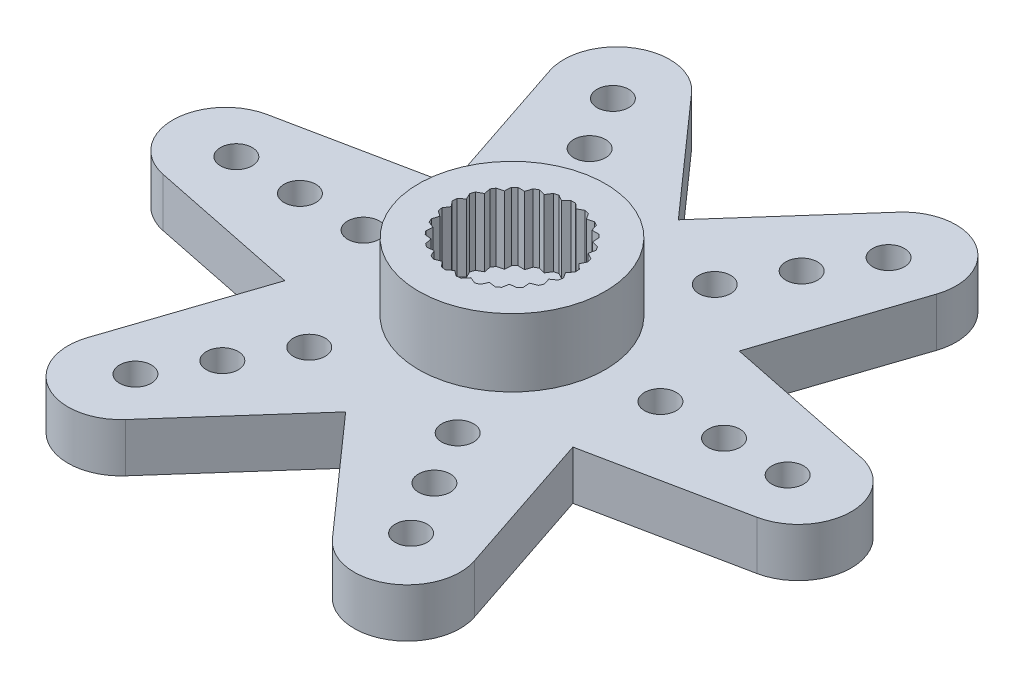
SolidWorks part; units mm, degrees
material "ABS"
ref_plane "Front Plane" through (0, 0, 0) normal (0, 0, 1) x (1, 0, 0)
ref_plane "Top Plane" through (0, 0, 0) normal (0, 1, 0) x (1, 0, 0)
ref_plane "Right Plane" through (0, 0, 0) normal (1, 0, 0) x (0, 0, -1)
sketch "Sketch2" plane through (0, 0, 0) normal (0, 1, 0) x (1, 0, 0)
  circle A0 centre (0, 0) radius 6
  circle A1 centre (0, 0) radius 1.5
  dimension "D1" = 12
  dimension "D2" = 3
extrude "Boss-Extrude1" add sketch "Sketch2" along normal mid plane 2.3
sketch "Sketch3" plane through (0, 1.15, 0) normal (0, 1, 0) x (1, 0, 0)
  line L0 (0, 0) -> (0, 2.9) construction
  line L3 (0, 0) -> (0.376, 2.9763) construction
  line L52 (0.1074, 2.898) -> (0.3384, 2.6787)
  line L53 (-0.1074, 2.898) -> (-0.3384, 2.6787)
  line L54 (0.8248, 2.7802) -> (0.9939, 2.5104)
  line L55 (0.6167, 2.8337) -> (0.3384, 2.6787)
  line L56 (1.4903, 2.4878) -> (1.587, 2.1843)
  line L57 (1.302, 2.5913) -> (0.9939, 2.5104)
  line L58 (2.0621, 2.039) -> (2.0804, 1.721)
  line L59 (1.9055, 2.1861) -> (1.587, 2.1843)
  line L60 (2.5044, 1.4621) -> (2.443, 1.1496)
  line L61 (2.3893, 1.6435) -> (2.0804, 1.721)
  line L62 (2.7894, 0.7934) -> (2.6522, 0.5059)
  line L63 (2.723, 0.9977) -> (2.443, 1.1496)
  line L64 (2.899, 0.0748) -> (2.6947, -0.1695)
  line L65 (2.8855, 0.2892) -> (2.6522, 0.5059)
  line L66 (2.8265, -0.6486) -> (2.5679, -0.8343)
  line L67 (2.8668, -0.4375) -> (2.6947, -0.1695)
  line L68 (2.5765, -1.3311) -> (2.2797, -1.4467)
  line L69 (2.6679, -1.1367) -> (2.5679, -0.8343)
  line L70 (2.1645, -1.93) -> (1.8483, -1.9682)
  line L71 (2.3014, -1.7645) -> (2.2797, -1.4467)
  line L72 (1.6165, -2.4077) -> (1.3007, -2.366)
  line L73 (1.7903, -2.2814) -> (1.8483, -1.9682)
  line L74 (0.967, -2.734) -> (0.6715, -2.6152)
  line L75 (1.1667, -2.655) -> (1.3007, -2.366)
  line L76 (0.2566, -2.8886) -> (0, -2.7)
  line L77 (0.4698, -2.8617) -> (0.6715, -2.6152)
  line L78 (-0.4698, -2.8617) -> (-0.6715, -2.6152)
  line L79 (-0.2566, -2.8886) -> (0, -2.7)
  line L80 (-1.1667, -2.655) -> (-1.3007, -2.366)
  line L81 (-0.967, -2.734) -> (-0.6715, -2.6152)
  line L82 (-1.7903, -2.2814) -> (-1.8483, -1.9682)
  line L83 (-1.6165, -2.4077) -> (-1.3007, -2.366)
  line L84 (-2.3014, -1.7645) -> (-2.2797, -1.4467)
  line L85 (-2.1645, -1.93) -> (-1.8483, -1.9682)
  line L86 (-2.6679, -1.1367) -> (-2.5679, -0.8343)
  line L87 (-2.5765, -1.3311) -> (-2.2797, -1.4467)
  line L88 (-2.8668, -0.4375) -> (-2.6947, -0.1695)
  line L89 (-2.8265, -0.6486) -> (-2.5679, -0.8343)
  line L90 (-2.8855, 0.2892) -> (-2.6522, 0.5059)
  line L91 (-2.899, 0.0748) -> (-2.6947, -0.1695)
  line L92 (-2.723, 0.9977) -> (-2.443, 1.1496)
  line L93 (-2.7894, 0.7934) -> (-2.6522, 0.5059)
  line L94 (-2.3893, 1.6435) -> (-2.0804, 1.721)
  line L95 (-2.5044, 1.4621) -> (-2.443, 1.1496)
  line L96 (-1.9055, 2.1861) -> (-1.587, 2.1843)
  line L97 (-2.0621, 2.039) -> (-2.0804, 1.721)
  line L98 (-1.302, 2.5913) -> (-0.9939, 2.5104)
  line L99 (-1.4903, 2.4878) -> (-1.587, 2.1843)
  line L100 (-0.6167, 2.8337) -> (-0.3384, 2.6787)
  line L101 (-0.8248, 2.7802) -> (-0.9939, 2.5104)
  line L102 (-2.533, 1.6075) -> (-2.3893, 1.6435) construction
  line L103 (-2.533, 1.6075) -> (-2.5044, 1.4621) construction
  line L104 (-2.8532, 0.9271) -> (-2.723, 0.9977) construction
  line L105 (-2.8532, 0.9271) -> (-2.7894, 0.7934) construction
  line L106 (-2.9941, 0.1884) -> (-2.8855, 0.2892) construction
  line L107 (-2.9941, 0.1884) -> (-2.899, 0.0748) construction
  line L108 (-2.9469, -0.5621) -> (-2.8668, -0.4375) construction
  line L109 (-2.9469, -0.5621) -> (-2.8265, -0.6486) construction
  line L110 (0, 3) -> (0.1074, 2.898) construction
  line L111 (0, 2.9) -> (0, 3) construction
  line L112 (0, 3) -> (-0.1074, 2.898) construction
  line L113 (-0.7461, 2.9057) -> (-0.6167, 2.8337) construction
  line L114 (-0.7461, 2.9057) -> (-0.8248, 2.7802) construction
  line L115 (-1.4453, 2.6289) -> (-1.302, 2.5913) construction
  line L116 (-1.4453, 2.6289) -> (-1.4903, 2.4878) construction
  line L117 (-2.0536, 2.1869) -> (-1.9055, 2.1861) construction
  line L118 (-2.0536, 2.1869) -> (-2.0621, 2.039) construction
  line L119 (-2.7145, -1.2773) -> (-2.6679, -1.1367) construction
  line L120 (-2.7145, -1.2773) -> (-2.5765, -1.3311) construction
  line L121 (-2.3115, -1.9123) -> (-2.3014, -1.7645) construction
  line L122 (-2.3115, -1.9123) -> (-2.1645, -1.93) construction
  line L123 (-1.7634, -2.4271) -> (-1.7903, -2.2814) construction
  line L124 (-1.7634, -2.4271) -> (-1.6165, -2.4077) construction
  line L125 (-1.1044, -2.7893) -> (-1.1667, -2.655) construction
  line L126 (-1.1044, -2.7893) -> (-0.967, -2.734) construction
  line L127 (-0.376, -2.9763) -> (-0.4698, -2.8617) construction
  line L128 (-0.376, -2.9763) -> (-0.2566, -2.8886) construction
  line L129 (0.376, -2.9763) -> (0.2566, -2.8886) construction
  line L130 (0.376, -2.9763) -> (0.4698, -2.8617) construction
  line L131 (1.1044, -2.7893) -> (0.967, -2.734) construction
  line L132 (1.1044, -2.7893) -> (1.1667, -2.655) construction
  line L133 (1.7634, -2.4271) -> (1.6165, -2.4077) construction
  line L134 (1.7634, -2.4271) -> (1.7903, -2.2814) construction
  line L135 (2.3115, -1.9123) -> (2.3014, -1.7645) construction
  line L136 (2.3115, -1.9123) -> (2.1645, -1.93) construction
  line L137 (2.7145, -1.2773) -> (2.6679, -1.1367) construction
  line L138 (2.7145, -1.2773) -> (2.5765, -1.3311) construction
  line L139 (2.9469, -0.5621) -> (2.8668, -0.4375) construction
  line L140 (2.9469, -0.5621) -> (2.8265, -0.6486) construction
  line L141 (2.9941, 0.1884) -> (2.8855, 0.2892) construction
  line L142 (2.9941, 0.1884) -> (2.899, 0.0748) construction
  line L143 (2.8532, 0.9271) -> (2.723, 0.9977) construction
  line L144 (2.8532, 0.9271) -> (2.7894, 0.7934) construction
  line L145 (2.533, 1.6075) -> (2.3893, 1.6435) construction
  line L146 (2.533, 1.6075) -> (2.5044, 1.4621) construction
  line L147 (2.0536, 2.1869) -> (1.9055, 2.1861) construction
  line L148 (2.0536, 2.1869) -> (2.0621, 2.039) construction
  line L149 (1.4453, 2.6289) -> (1.302, 2.5913) construction
  line L150 (1.4453, 2.6289) -> (1.4903, 2.4878) construction
  line L151 (0.7461, 2.9057) -> (0.6167, 2.8337) construction
  line L152 (0.7461, 2.9057) -> (0.8248, 2.7802) construction
  circle A0 centre (0, 0) radius 4.4
  circle A1 centre (0, 0) radius 3 construction
  circle A2 centre (0, 0) radius 2.7 construction
  arc A3 (-0.6167, 2.8337) -> (-0.8248, 2.7802) centre (0, 0) ccw
  arc A4 (-0.1074, 2.898) -> (-0.6167, 2.8337) centre (0, 0) ccw construction
  arc A5 (-0.8248, 2.7802) -> (-1.302, 2.5913) centre (0, 0) ccw construction
  arc A6 (-1.302, 2.5913) -> (-1.4903, 2.4878) centre (0, 0) ccw
  arc A7 (-1.4903, 2.4878) -> (-1.9055, 2.1861) centre (0, 0) ccw construction
  arc A8 (-1.9055, 2.1861) -> (-2.0621, 2.039) centre (0, 0) ccw
  arc A9 (-2.0621, 2.039) -> (-2.3893, 1.6435) centre (0, 0) ccw construction
  arc A10 (-2.3893, 1.6435) -> (-2.5044, 1.4621) centre (0, 0) ccw
  arc A11 (-2.5044, 1.4621) -> (-2.723, 0.9977) centre (0, 0) ccw construction
  arc A12 (-2.723, 0.9977) -> (-2.7894, 0.7934) centre (0, 0) ccw
  arc A13 (-2.7894, 0.7934) -> (-2.8855, 0.2892) centre (0, 0) ccw construction
  arc A14 (-2.8855, 0.2892) -> (-2.899, 0.0748) centre (0, 0) ccw
  arc A15 (-2.899, 0.0748) -> (-2.8668, -0.4375) centre (0, 0) ccw construction
  arc A16 (-2.8668, -0.4375) -> (-2.8265, -0.6486) centre (0, 0) ccw
  arc A17 (-2.8265, -0.6486) -> (-2.6679, -1.1367) centre (0, 0) ccw construction
  arc A18 (-2.6679, -1.1367) -> (-2.5765, -1.3311) centre (0, 0) ccw
  arc A19 (-2.5765, -1.3311) -> (-2.3014, -1.7645) centre (0, 0) ccw construction
  arc A20 (-2.3014, -1.7645) -> (-2.1645, -1.93) centre (0, 0) ccw
  arc A21 (-2.1645, -1.93) -> (-1.7903, -2.2814) centre (0, 0) ccw construction
  arc A22 (-1.7903, -2.2814) -> (-1.6165, -2.4077) centre (0, 0) ccw
  arc A23 (-1.6165, -2.4077) -> (-1.1667, -2.655) centre (0, 0) ccw construction
  arc A24 (-1.1667, -2.655) -> (-0.967, -2.734) centre (0, 0) ccw
  arc A25 (-0.967, -2.734) -> (-0.4698, -2.8617) centre (0, 0) ccw construction
  arc A26 (-0.4698, -2.8617) -> (-0.2566, -2.8886) centre (0, 0) ccw
  arc A27 (-0.2566, -2.8886) -> (0.2566, -2.8886) centre (0, 0) ccw construction
  arc A28 (0.2566, -2.8886) -> (0.4698, -2.8617) centre (0, 0) ccw
  arc A29 (0.4698, -2.8617) -> (0.967, -2.734) centre (0, 0) ccw construction
  arc A30 (0.967, -2.734) -> (1.1667, -2.655) centre (0, 0) ccw
  arc A31 (1.1667, -2.655) -> (1.6165, -2.4077) centre (0, 0) ccw construction
  arc A32 (1.6165, -2.4077) -> (1.7903, -2.2814) centre (0, 0) ccw
  arc A33 (1.7903, -2.2814) -> (2.1645, -1.93) centre (0, 0) ccw construction
  arc A34 (2.1645, -1.93) -> (2.3014, -1.7645) centre (0, 0) ccw
  arc A35 (2.3014, -1.7645) -> (2.5765, -1.3311) centre (0, 0) ccw construction
  arc A36 (2.5765, -1.3311) -> (2.6679, -1.1367) centre (0, 0) ccw
  arc A37 (2.6679, -1.1367) -> (2.8265, -0.6486) centre (0, 0) ccw construction
  arc A38 (2.8265, -0.6486) -> (2.8668, -0.4375) centre (0, 0) ccw
  arc A39 (2.8668, -0.4375) -> (2.899, 0.0748) centre (0, 0) ccw construction
  arc A40 (2.899, 0.0748) -> (2.8855, 0.2892) centre (0, 0) ccw
  arc A41 (2.8855, 0.2892) -> (2.7894, 0.7934) centre (0, 0) ccw construction
  arc A42 (2.7894, 0.7934) -> (2.723, 0.9977) centre (0, 0) ccw
  arc A43 (2.723, 0.9977) -> (2.5044, 1.4621) centre (0, 0) ccw construction
  arc A44 (2.5044, 1.4621) -> (2.3893, 1.6435) centre (0, 0) ccw
  arc A45 (2.3893, 1.6435) -> (2.0621, 2.039) centre (0, 0) ccw construction
  arc A46 (2.0621, 2.039) -> (1.9055, 2.1861) centre (0, 0) ccw
  arc A47 (1.9055, 2.1861) -> (1.4903, 2.4878) centre (0, 0) ccw construction
  arc A48 (1.4903, 2.4878) -> (1.302, 2.5913) centre (0, 0) ccw
  arc A49 (1.302, 2.5913) -> (0.8248, 2.7802) centre (0, 0) ccw construction
  arc A50 (0.8248, 2.7802) -> (0.6167, 2.8337) centre (0, 0) ccw
  arc A51 (0.3635, 2.8771) -> (0.1074, 2.898) centre (0, 0) ccw construction
  arc A52 (0.1074, 2.898) -> (-0.1074, 2.898) centre (0, 0) ccw
  arc A53 (0.6167, 2.8337) -> (0.3635, 2.8771) centre (0, 0) ccw construction
  point P84 (0, 0)
  dimension "D1" = 8.8
  dimension "D2" = 5.4
  dimension "D3" = 6
  dimension "D6" = 5.8
  dimension "D4" = 7.2
  dimension "D5" = 25
extrude "Boss-Extrude2" add sketch "Sketch3" along normal blind 3.2
sketch "Sketch4" plane through (0, 0, 0) normal (0, 1, 0) x (1, 0, 0)
  line L0 (0, 0) -> (13, 0) construction
  line L1 (3.9686, 4.5) -> (14.0007, 2.4494)
  line L2 (3.9686, -4.5) -> (14.0007, -2.4494)
  line L3 (13, 0) -> (10, 0) construction
  circle A0 centre (0, 0) radius 6 construction
  arc A1 (3.9686, -4.5) -> (3.9686, 4.5) centre (0, 0) ccw
  arc A2 (14.0007, 2.4494) -> (14.0007, -2.4494) centre (13.5, 0) cw
  circle A3 centre (13, 0) radius 0.75
  circle A4 centre (10, 0) radius 0.75
  circle A5 centre (7, 0) radius 0.75
  dimension "D3" = 2.5
  dimension "D5" = 1.5
  dimension "D2" = 9
  dimension "D7" = 3
  dimension "D4" = 0.5
  dimension "D1" = 13
  dimension "D6" = 3
extrude "Boss-Extrude3" add sketch "Sketch4" along normal mid plane 2.3
pattern_circular "CirPattern1" count 6 over 360 about axis through (0, 0, 0) along (0, 1, 0) of "Boss-Extrude3"
sketch "Sketch5" [suppressed] plane through (0, 0, 0) normal (0, 1, 0) x (1, 0, 0)
  line L0 (3, 7) -> (-3, 7) construction
  circle A0 centre (0, 0) radius 10
  circle A1 centre (0, 7) radius 0.75
  circle A2 centre (-3, 7) radius 0.75
  circle A3 centre (3, 7) radius 0.75
  circle A4 centre (7, 3) radius 0.75
  circle A5 centre (7, 0) radius 0.75
  circle A6 centre (7, -3) radius 0.75
  circle A7 centre (3, -7) radius 0.75
  circle A8 centre (0, -7) radius 0.75
  circle A9 centre (-3, -7) radius 0.75
  circle A10 centre (-7, -3) radius 0.75
  circle A11 centre (-7, 0) radius 0.75
  circle A12 centre (-7, 3) radius 0.75
  circle A13 centre (0, 0) radius 1.5 construction
  circle A14 centre (0, 0) radius 1.5
  point P8 (0, 7)
  point P31 (0, 0)
  dimension "D1" = 1.5
  dimension "D3" = 2.25
  dimension "D4" = 6
  dimension "D2" = 7
  dimension "D5" = 4
extrude "Boss-Extrude4" [suppressed] add sketch "Sketch5" along normal mid plane 2.3
equation "\"N_hole\"= 3"
equation "\"N_horn\"= 6"
equation "\"D6@Sketch4\"=\"N_hole\""
equation "\"D1@CirPattern1\"=\"N_horn\""
equation "\"D1@Sketch4\"=(\"N_hole\" - 1) *3 +7"
